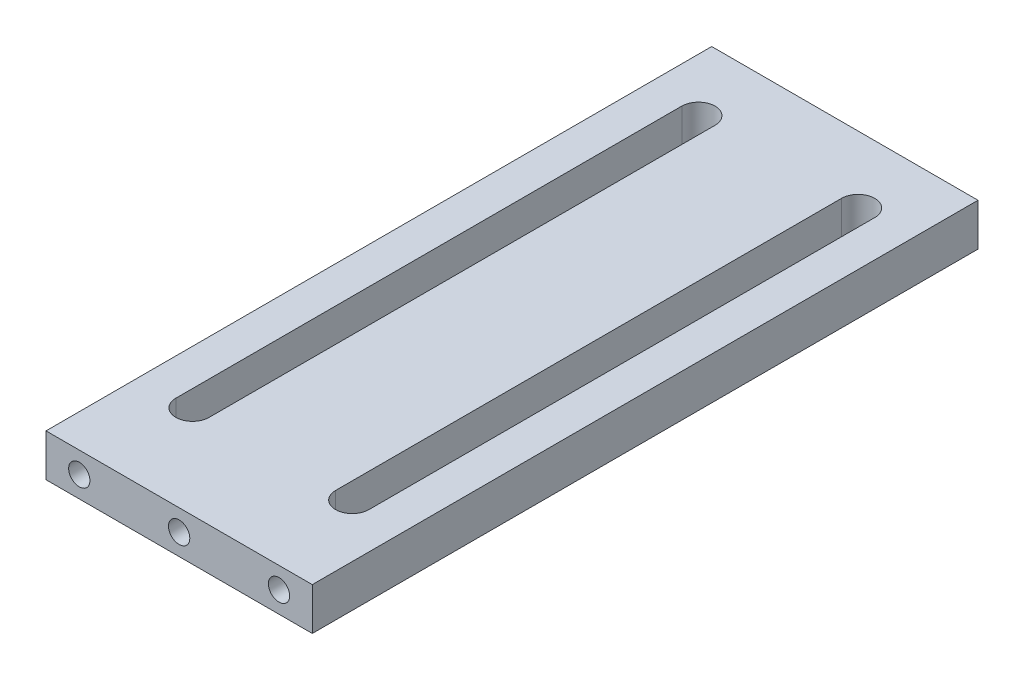
SolidWorks part; units mm, degrees
ref_plane "Front Plane" through (0, 0, 0) normal (0, 0, 1) x (1, 0, 0)
ref_plane "Top Plane" through (0, 0, 0) normal (0, 1, 0) x (1, 0, 0)
ref_plane "Right Plane" through (0, 0, 0) normal (1, 0, 0) x (0, 0, -1)
sketch "Sketch1" plane through (0, 0, 0) normal (0, 1, 0) x (1, 0, 0)
  line L1 (0, 0) -> (20, 0)
  line L2 (0, 0) -> (0, 50)
  line L3 (0, 50) -> (20, 50)
  line L4 (20, 0) -> (20, 50)
  dimension "D1" = 20
  dimension "D2" = 50
extrude "Boss-Extrude1" add sketch "Sketch1" along normal blind 3.18
sketch "Sketch2" plane through (0, 3.18, 0) normal (0, 1, 0) x (1, 0, 0)
  line L0 (4, 7) -> (4, 45) construction
  line L1 (2.75, 7) -> (2.75, 45)
  line L2 (5.25, 7) -> (5.25, 45)
  line L3 (10, 50) -> (10, 0) construction
  line L4 (20, 50) -> (0, 50) construction
  line L5 (0, 0) -> (20, 0) construction
  arc A0 (2.75, 7) -> (5.25, 7) centre (4, 7) ccw
  arc A1 (5.25, 45) -> (2.75, 45) centre (4, 45) ccw
  point P2 (4, 26)
  dimension "D2" = 2.5
  dimension "D1" = 6
  dimension "D3" = 7
  dimension "D4" = 5
extrude "Cut-Extrude1" cut sketch "Sketch2" against normal through all
ref_plane "Plane1" through (10, 0, 0) normal (1, 0, 0) x (0, 0, -1)
mirror "Mirror1" about plane through (10, 0, 0) normal (1, 0, 0) of "Cut-Extrude1"
sketch "Sketch3" plane through (0, 0, 0) normal (0, 0, 1) x (1, 0, 0)
  line L0 (0, 1.59) -> (20, 1.59) construction
  line L1 (0, 3.18) -> (0, 0) construction
  line L2 (20, 3.18) -> (20, 0) construction
  circle A0 centre (10, 1.59) radius 0.8
  circle A1 centre (2.5, 1.59) radius 0.8
  circle A2 centre (17.5, 1.59) radius 0.8
  dimension "D1" = 1.6
  dimension "D2" = 1.6
  dimension "D3" = 1.6
  dimension "D4" = 2.5
  dimension "D5" = 2.5
extrude "Cut-Extrude2" cut sketch "Sketch3" against normal blind 4
